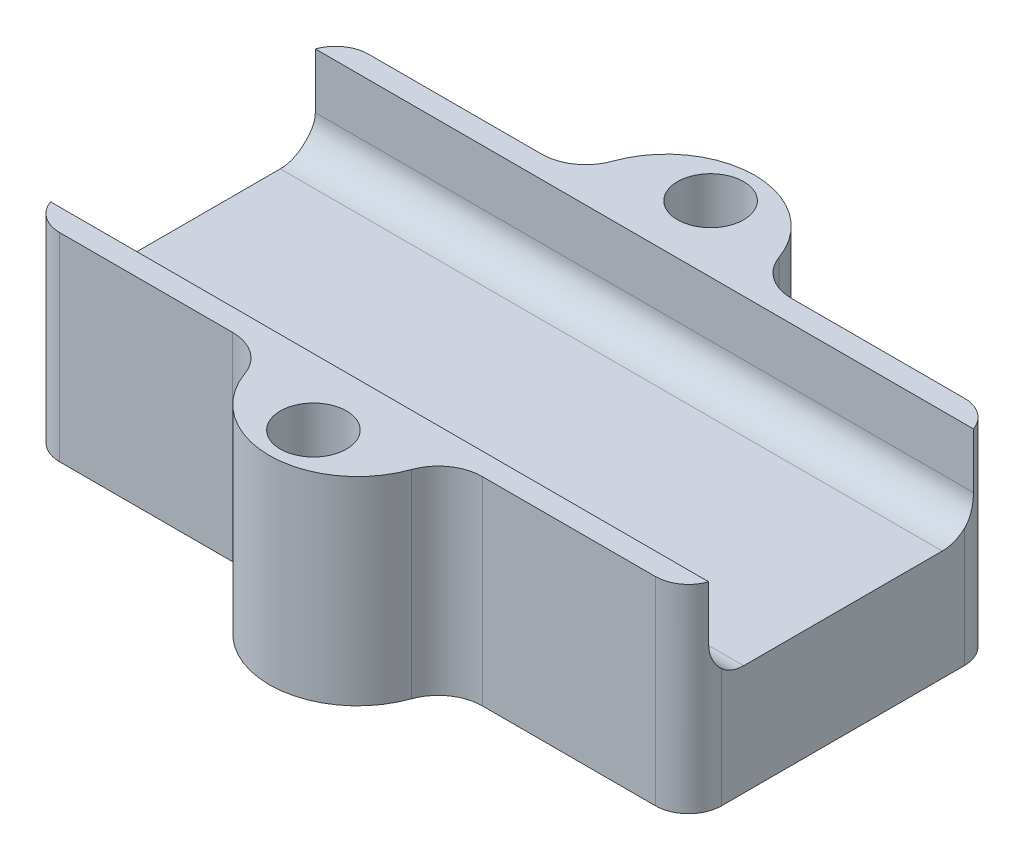
SolidWorks part; units mm, degrees
ref_plane "Front Plane" through (0, 0, 0) normal (0, 0, 1) x (1, 0, 0)
ref_plane "Top Plane" through (0, 0, 0) normal (0, 1, 0) x (1, 0, 0)
ref_plane "Right Plane" through (0, 0, 0) normal (1, 0, 0) x (0, 0, -1)
sketch "Sketch1" plane through (0, 0, 0) normal (0, 1, 0) x (1, 0, 0)
  line L0 (-1000, 0) -> (49000, 0) construction
  line L1 (-15, 7) -> (-4, 7)
  line L2 (-15, 7) -> (-15, -7)
  line L3 (-15, -7) -> (-4, -7)
  line L4 (15, 7) -> (15, -7)
  line L5 (-15, 7) -> (15, -7) construction
  line L6 (-15, -7) -> (15, 7) construction
  line L7 (4, 7) -> (15, 7)
  line L8 (4, -7) -> (15, -7)
  arc A0 (-4, -7) -> (4, -7) centre (0, -7) ccw
  arc A2 (-4, 7) -> (4, 7) centre (0, 7) cw
  point P0 (0, 0)
  point P6 (0, 0)
  point P15 (0, 0)
  point P16 (0, 0)
  dimension "D3" = 15
  dimension "D1" = 30
  dimension "D2" = 14
extrude "Boss-Extrude1" add sketch "Sketch1" along normal blind 9
sketch "Sketch2" plane through (0, 9, 0) normal (0, 1, 0) x (1, 0, 0)
  line L0 (15, -7) -> (15, 7) construction
  line L1 (-15, 6) -> (15, 6)
  line L2 (-15, 6) -> (-15, -6)
  line L3 (-15, -6) -> (15, -6)
  line L4 (15, 6) -> (15, -6)
  line L5 (-15, 6) -> (15, -6) construction
  line L6 (-15, -6) -> (15, 6) construction
  point P0 (0, 0)
  dimension "D1" = 12
extrude "Cut-Extrude1" cut sketch "Sketch2" against normal blind 4
fillet "Fillet1" radius 2 4 edges at (-4, 4.5, 7) (4, 4.5, 7) (-4, 4.5, -7) (4, 4.5, -7)
fillet "Fillet2" radius 1.5 4 edges at (15, 4.5, -7) (15, 4.5, 7) (-15, 4.5, 7) (-15, 4.5, -7)
sketch "Sketch3" plane through (0, 0, 0) normal (0, -1, 0) x (1, 0, 0)
  line L0 (0, -1000) -> (0, 49000) construction
  line L1 (5.6569, 7) -> (13.5, 7) construction
  circle A0 centre (0, 9) radius 1.5
  circle A1 centre (0, -9) radius 1.5
  dimension "D1" = 3
  dimension "D2" = 3
  dimension "D3" = 18
  dimension "D4" = 2
extrude "Cut-Extrude2" cut sketch "Sketch3" against normal through all
sketch "Sketch5" plane through (-15, 0, 0) normal (-1, 0, 0) x (0, 0, 1)
  text T0 "MICO" height 2.5
extrude "Boss-Extrude2" add sketch "Sketch5" along normal blind 0.8
fillet "Fillet3" radius 1.5 2 edges at (0, 5, 6) (0, 5, -6)
